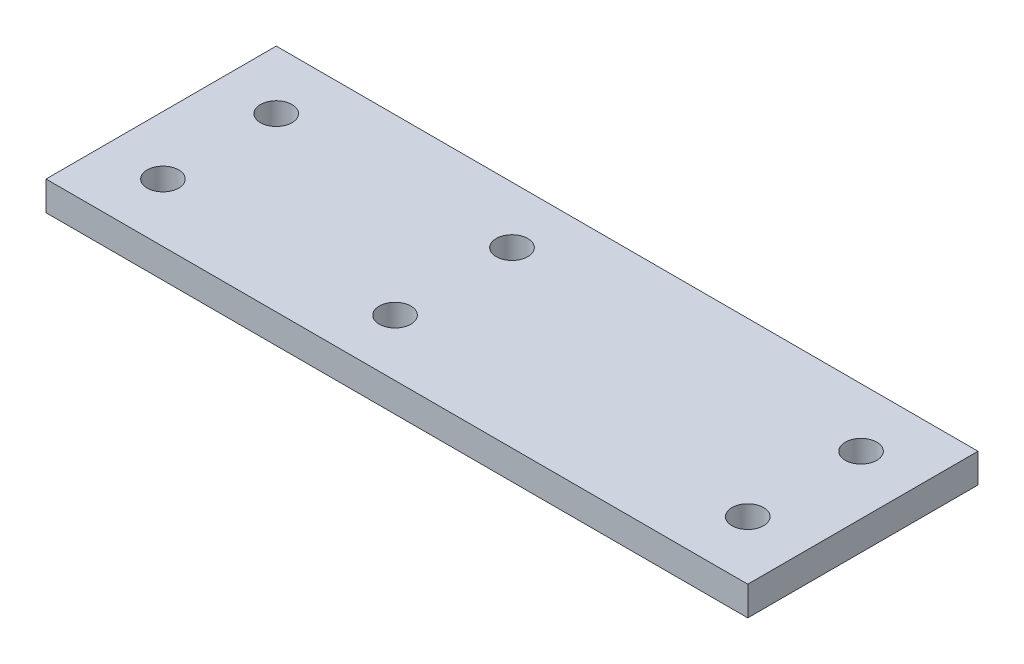
SolidWorks part; units mm, degrees
material "6061 Alloy"
ref_plane "Front Plane" through (0, 0, 0) normal (0, 0, 1) x (1, 0, 0)
ref_plane "Top Plane" through (0, 0, 0) normal (0, 1, 0) x (1, 0, 0)
ref_plane "Right Plane" through (0, 0, 0) normal (1, 0, 0) x (0, 0, -1)
sketch "Sketch1" plane through (0, 0, 0) normal (0, 1, 0) x (1, 0, 0)
  line L1 (-76.2, 25) -> (76.2, 25)
  line L2 (-76.2, 25) -> (-76.2, -25)
  line L3 (-76.2, -25) -> (76.2, -25)
  line L4 (76.2, 25) -> (76.2, -25)
  line L5 (-76.2, 25) -> (76.2, -25) construction
  line L6 (-76.2, -25) -> (76.2, 25) construction
  point P0 (0, 0)
  dimension "D1" = 50
  dimension "D2" = 152.4
extrude "Boss-Extrude1" add sketch "Sketch1" along normal blind 6.35
sketch "Sketch3" plane through (0, 0, 0) normal (0, -1, 0) x (1, 0, 0)
  line L0 (0, 0) -> (0, -20.7585) construction
  line L1 (0, 0) -> (-13.1006, 0) construction
  line L2 (-76.2, -25) -> (-76.2, 25) construction
  line L3 (-76.2, 25) -> (76.2, 25) construction
  line L4 (76.2, -25) -> (-76.2, -25) construction
  circle A0 centre (-63.5, 12.3) radius 3.429
  circle A1 centre (-63.5, -12.3) radius 3.429
  circle A2 centre (63.5, 12.3) radius 3.429
  circle A3 centre (63.5, -12.3) radius 3.429
  circle A4 centre (-12.699, 12.7) radius 3.429
  circle A5 centre (-12.699, -12.7) radius 3.429
  dimension "D1" = 12.7
  dimension "D4" = 76.2
  dimension "D5" = 76.2
  dimension "D2" = 12.7
  dimension "D3" = 12.7
extrude "Cut-Extrude2" cut sketch "Sketch3" against normal up to next
